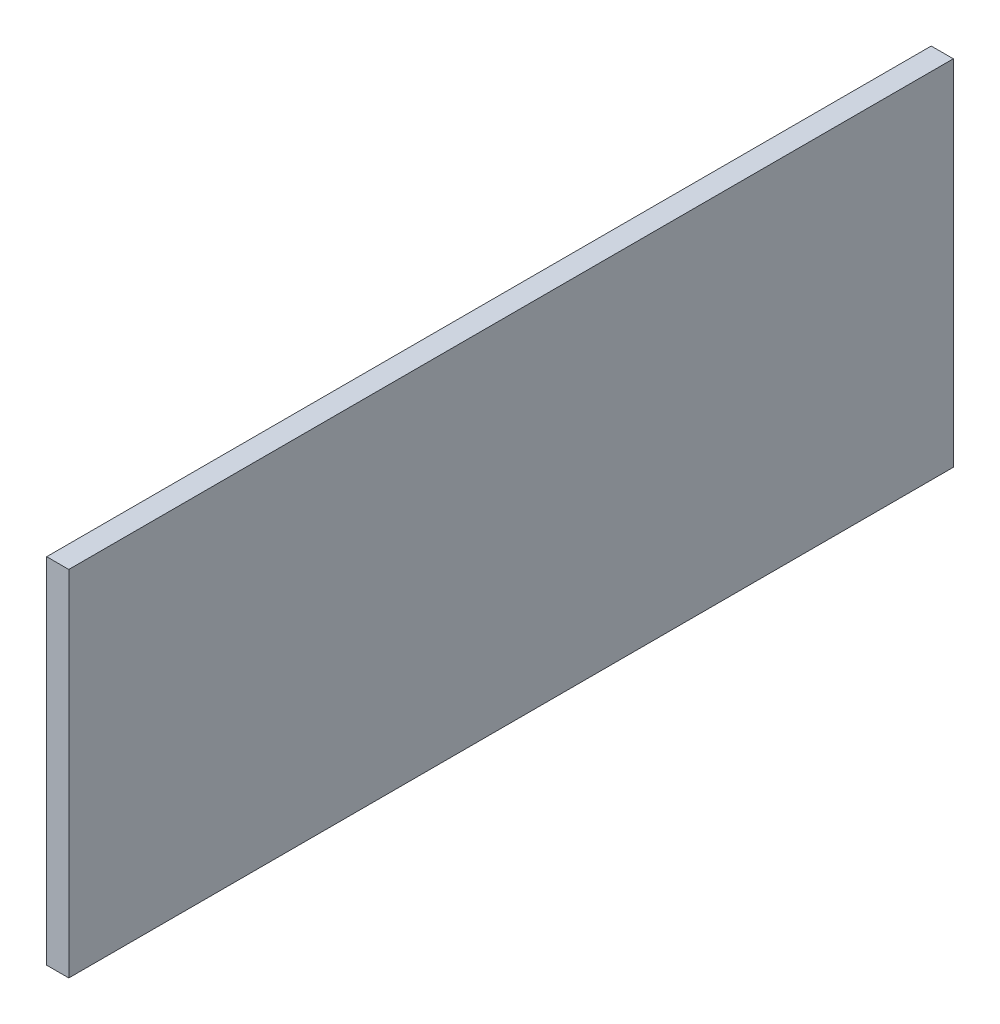
SolidWorks part; units mm, degrees
ref_plane "Plan de face" through (0, 0, 0) normal (0, 0, 1) x (1, 0, 0)
ref_plane "Plan de dessus" through (0, 0, 0) normal (0, 1, 0) x (1, 0, 0)
ref_plane "Plan de droite" through (0, 0, 0) normal (1, 0, 0) x (0, 0, -1)
sketch "Esquisse1" plane through (0, 0, 0) normal (0, 1, 0) x (1, 0, 0)
  line L0 (0, -55) -> (0, 55) construction
  line L1 (-2.5, 100) -> (2.5, 100)
  line L2 (-2.5, 100) -> (-2.5, -100)
  line L3 (-2.5, -100) -> (2.5, -100)
  line L4 (2.5, 100) -> (2.5, -100)
  line L5 (-55, 0) -> (55, 0) construction
  dimension "D1" = 5
  dimension "D2" = 200
  dimension "D3" = 2.5
  dimension "D4" = 100
extrude "Boss.-Extru.1" add sketch "Esquisse1" along normal blind 80
